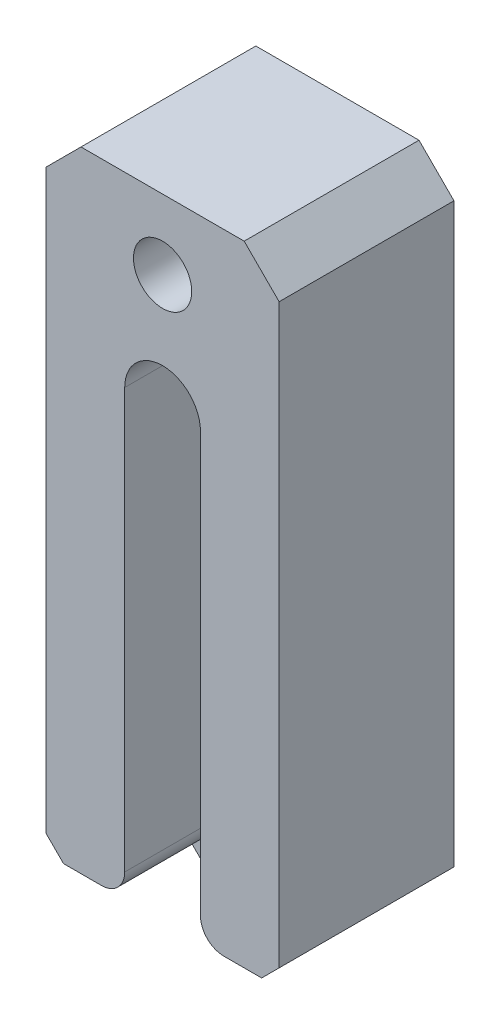
SolidWorks part; units mm, degrees
ref_plane "Plan de face" through (0, 0, 0) normal (0, 0, 1) x (1, 0, 0)
ref_plane "Plan de dessus" through (0, 0, 0) normal (0, 1, 0) x (1, 0, 0)
ref_plane "Plan de droite" through (0, 0, 0) normal (1, 0, 0) x (0, 0, -1)
sketch "Esquisse1" plane through (0, 0, 0) normal (0, 0, 1) x (1, 0, 0)
  line L1 (0, 0) -> (20, 0)
  line L2 (0, 0) -> (0, 60)
  line L3 (0, 60) -> (20, 60)
  line L4 (20, 0) -> (20, 60)
  dimension "D1" = 20
  dimension "D2" = 60
extrude "Boss.-Extru.1" add sketch "Esquisse1" along normal blind 15
sketch "Esquisse2" plane through (0, 0, 15) normal (0, 0, 1) x (1, 0, 0)
  line L0 (10, 0) -> (10, 60) construction
  line L1 (0, 0) -> (20, 0) construction
  line L2 (20, 60) -> (0, 60) construction
  line L3 (10, 12) -> (10, 44) construction
  line L4 (6.75, 12) -> (6.75, 44)
  line L5 (13.25, 12) -> (13.25, 44)
  arc A0 (6.75, 12) -> (13.25, 12) centre (10, 12) ccw
  arc A1 (13.25, 44) -> (6.75, 44) centre (10, 44) ccw
  circle A2 centre (10, 54) radius 2.5
  point P8 (10, 28)
  dimension "D4" = 5
  dimension "D1" = 6.5
  dimension "D2" = 32
  dimension "D3" = 12
  dimension "D5" = 6
extrude "Enlèv. mat.-Extru.1" cut sketch "Esquisse2" against normal up to vertex (15 mm away) up to point (20, 60, 0)
sketch "Esquisse3" plane through (0, 0, 15) normal (0, 0, 1) x (1, 0, 0)
  line L0 (0, 6) -> (20, 6)
  line L1 (0, 60) -> (0, 0) construction
  line L2 (20, 0) -> (20, 60) construction
  line L3 (20, 6) -> (20, 0)
  line L4 (20, 0) -> (0, 0)
  line L5 (0, 0) -> (0, 6)
  dimension "D1" = 6
extrude "Enlèv. mat.-Extru.2" cut sketch "Esquisse3" against normal blind 9
sketch "Esquisse6" plane through (0, 0, 15) normal (0, 0, 1) x (1, 0, 0)
  line L0 (7.5, 0) -> (0, 7.5)
  line L1 (0, 0) -> (20, 0) construction
  line L2 (0, 60) -> (0, 6) construction
  line L3 (0, 7.5) -> (0, -7.5)
  line L4 (0, -7.5) -> (20, -7.5)
  line L5 (20, -7.5) -> (20, 7.5)
  line L6 (20, 7.5) -> (12.5, 0)
  line L7 (12.5, 0) -> (7.5, 0)
  line L8 (10, 8.75) -> (10, 0) construction
  line L9 (20, 6) -> (20, 60) construction
  arc A0 (6.75, 12) -> (13.25, 12) centre (10, 12) ccw construction
  dimension "D1" = 5
  dimension "D2" = 15
extrude "Enlèv. mat.-Extru.3" cut sketch "Esquisse6" against normal up to vertex (15 mm away) up to point (20, 0, 0)
sketch "Esquisse7" plane through (0, 0, 15) normal (0, 0, 1) x (1, 0, 0)
  line L0 (6.75, 44) -> (6.75, 12) construction
  line L1 (6.75, 14) -> (13.25, 14)
  line L2 (6.75, 14) -> (6.75, 6)
  line L3 (6.75, 6) -> (13.25, 6)
  line L4 (13.25, 14) -> (13.25, 6)
  line L5 (18.5, 6) -> (1.5, 6) construction
  line L6 (13.25, 12) -> (13.25, 44) construction
  dimension "D1" = 8
extrude "Enlèv. mat.-Extru.4" cut sketch "Esquisse7" against normal up to vertex (9 mm away) up to point (12.5, 0, 6)
fillet "Congé1" radius 2 2 edges at (13.25, 6, 10.5) (6.75, 6, 10.5)
chamfer "Chanfrein1" distance 3 angle 45 2 edges at (20, 60, 7.5) (0, 60, 7.5)
